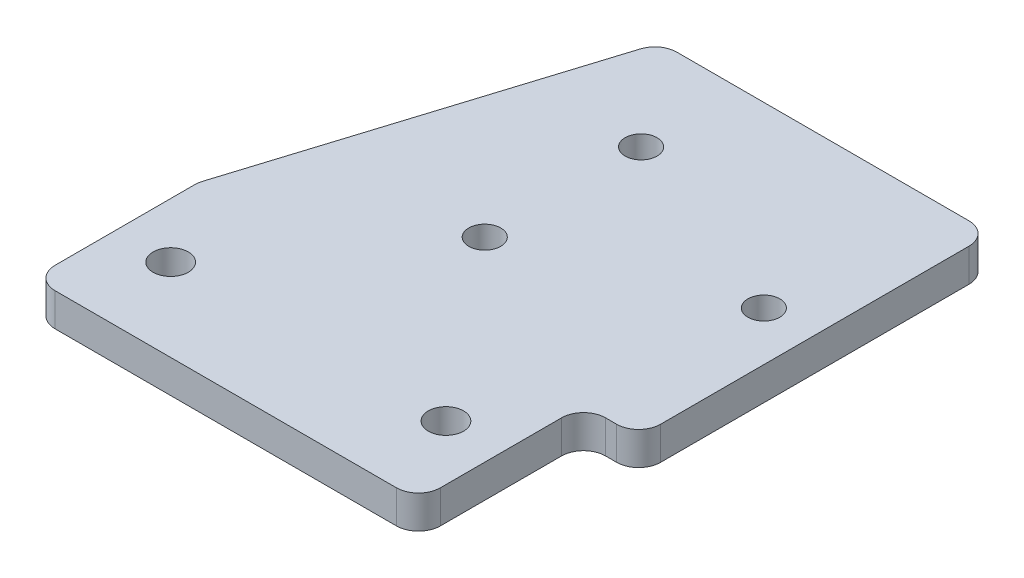
SolidWorks part; units mm, degrees
material "ABS"
ref_plane "前视基准面" through (0, 0, 0) normal (0, 0, 1) x (1, 0, 0)
ref_plane "上视基准面" through (0, 0, 0) normal (0, 1, 0) x (1, 0, 0)
ref_plane "右视基准面" through (0, 0, 0) normal (1, 0, 0) x (0, 0, -1)
other "Configuration Table"
sketch "草图1" plane through (0, 0, 0) normal (0, 1, 0) x (1, 0, 0)
  line L0 (0, 0) -> (35, 0) construction
  line L1 (0, 0) -> (0, 15) construction
  line L2 (0, 15) -> (35, 15) construction
  line L3 (35, 0) -> (35, 15) construction
  line L4 (0, 0) -> (35, 15) construction
  line L5 (0, 15) -> (35, 0) construction
  line L6 (10, 0) -> (25, 0) construction
  line L7 (10, 0) -> (10, 47) construction
  line L8 (10, 47) -> (25, 47) construction
  line L9 (25, 0) -> (25, 47) construction
  line L10 (0, 0) -> (0, 15)
  line L11 (0, 15) -> (10, 47)
  line L12 (10, 47) -> (25, 47)
  line L13 (25, 47) -> (35, 15) construction
  line L14 (35, 15) -> (35, 0)
  line L15 (35, 0) -> (0, 0)
  line L16 (17.3016, 30.8243) -> (35.5516, 30.8243) construction
  line L17 (25, 47) -> (40, 47)
  line L18 (40, 47) -> (40, 15)
  line L19 (40, 15) -> (35, 15)
  line L20 (5, 7.5) -> (30, 7.5) construction
  line L21 (17.3016, 37.9243) -> (17.3016, 23.7243) construction
  circle A0 centre (30, 7.5) radius 1.6
  circle A3 centre (5, 7.5) radius 1.6
  circle A7 centre (35.5516, 30.8243) radius 1.45
  circle A8 centre (17.3016, 37.9243) radius 1.45
  circle A9 centre (17.3016, 23.7243) radius 1.45
  point P0 (17.5, 7.5)
  point P18 (17.3016, 30.8243)
  point P21 (16.2289, 30.8243)
  point P22 (17.3016, 30.8243)
  dimension "D7" = 10
  dimension "D2" = 14.2
  dimension "D17" = 3.2
  dimension "D18" = 3.2
  dimension "D8" = 2.9
  dimension "D1" = 15
  dimension "D3" = 18.25
  dimension "D4" = 32
  dimension "D5" = 25
  dimension "D6" = 5
  dimension "D11" = 10
  dimension "D14" = 5
  dimension "D15" = 7.5
  dimension "D16" = 35
extrude "凸台-拉伸1" add sketch "草图1" along normal blind 3
fillet "圆角2" radius 2 7 edges at (0, 1.5, 0) (0, 1.5, -15) (10, 1.5, -47) (40, 1.5, -47) (40, 1.5, -15) (35, 1.5, 0) (35, 1.5, -15)
